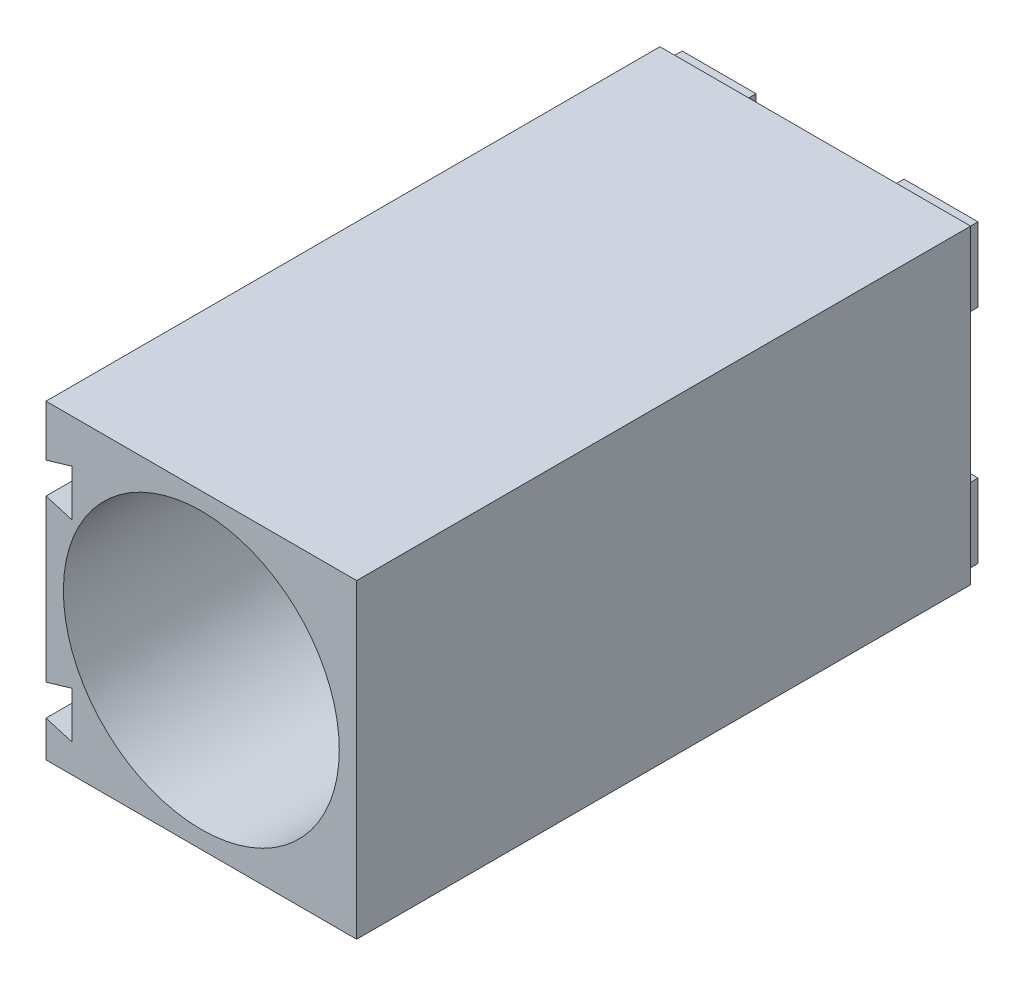
SolidWorks part; units mm, degrees
ref_plane "Front Plane" through (0, 0, 0) normal (0, 0, 1) x (1, 0, 0)
ref_plane "Top Plane" through (0, 0, 0) normal (0, 1, 0) x (1, 0, 0)
ref_plane "Right Plane" through (0, 0, 0) normal (1, 0, 0) x (0, 0, -1)
sketch "Croquis1" plane through (0, 0, 0) normal (0, 0, 1) x (1, 0, 0)
  line L0 (31.5, -10.5) -> (10.5, 10.5) construction
  line L1 (-10.5, 10.5) -> (31.5, 10.5)
  line L2 (-10.5, 10.5) -> (-10.5, -10.5)
  line L3 (-10.5, -10.5) -> (31.5, -10.5)
  line L4 (10.5, 10.5) -> (10.5, -10.5)
  line L5 (-10.5, 10.5) -> (10.5, -10.5) construction
  line L6 (-10.5, -10.5) -> (10.5, 10.5) construction
  line L7 (31.5, 10.5) -> (10.5, -10.5) construction
  line L8 (31.5, 10.5) -> (31.5, -10.5)
  circle A0 centre (0, 0) radius 9.325
  circle A1 centre (21, 0) radius 9.325
  point P0 (0, 0)
  point P12 (21, 0)
  dimension "D3" = 18.65
  dimension "D1" = 21
  dimension "D2" = 21
extrude "Saliente-Extruir1" add sketch "Croquis1" along normal mid plane 41.5 contours L4 L1 L2 L3 A0
sketch "Croquis2" plane through (0, 0, -20.75) normal (0, 0, -1) x (-1, 0, 0)
  line L0 (-10.5, 10.5) -> (-10.5, -10.5) construction
  line L1 (-10, 10) -> (-5, 10)
  line L2 (-10, 10) -> (-10, 5)
  line L3 (-10, 5) -> (-5, 5)
  line L4 (-5, 10) -> (-5, 5)
  line L5 (-10, 10) -> (-5, 5) construction
  line L6 (-10, 5) -> (-5, 10) construction
  line L7 (10.5, 10.5) -> (-10.5, 10.5) construction
  line L8 (0, 0) -> (10.5, 0) construction
  line L9 (10.5, 10.5) -> (10.5, -10.5) construction
  line L10 (0, 0) -> (0, 10.5) construction
  line L11 (10, 5) -> (5, 10) construction
  line L12 (10, 10) -> (5, 5) construction
  line L13 (5, 10) -> (5, 5)
  line L14 (10, 5) -> (5, 5)
  line L15 (10, 10) -> (10, 5)
  line L16 (10, 10) -> (5, 10)
  line L17 (10, -10) -> (5, -5) construction
  line L18 (10, -5) -> (5, -10) construction
  line L19 (10, -10) -> (5, -10)
  line L20 (10, -10) -> (10, -5)
  line L21 (10, -5) -> (5, -5)
  line L22 (5, -10) -> (5, -5)
  line L23 (-10, -5) -> (-5, -10) construction
  line L24 (-10, -10) -> (-5, -5) construction
  line L25 (-5, -10) -> (-5, -5)
  line L26 (-10, -5) -> (-5, -5)
  line L27 (-10, -10) -> (-10, -5)
  line L28 (-10, -10) -> (-5, -10)
  line L29 (-10.5, -10.5) -> (-10.5, 10.5) construction
  line L30 (-11, -10) -> (-16, -5) construction
  line L31 (-11, -5) -> (-16, -10) construction
  line L32 (-31, -5) -> (-26, -10) construction
  line L33 (-31, -10) -> (-26, -5) construction
  line L34 (-31, 10) -> (-26, 5) construction
  line L35 (-31, 5) -> (-26, 10) construction
  line L36 (-11, 5) -> (-16, 10) construction
  line L37 (-11, 10) -> (-16, 5) construction
  line L38 (-11, -10) -> (-16, -10)
  line L39 (-11, -10) -> (-11, -5)
  line L40 (-11, -5) -> (-16, -5)
  line L41 (-16, -10) -> (-16, -5)
  line L42 (-26, -10) -> (-26, -5)
  line L43 (-31, -5) -> (-26, -5)
  line L44 (-31, -10) -> (-31, -5)
  line L45 (-31, -10) -> (-26, -10)
  line L46 (-31, 10) -> (-26, 10)
  line L47 (-31, 10) -> (-31, 5)
  line L48 (-31, 5) -> (-26, 5)
  line L49 (-26, 10) -> (-26, 5)
  line L50 (-16, 10) -> (-16, 5)
  line L51 (-11, 5) -> (-16, 5)
  line L52 (-11, 10) -> (-11, 5)
  line L53 (-11, 10) -> (-16, 10)
  point P0 (-7.5, 7.5)
  point P19 (7.5, 7.5)
  point P24 (7.5, -7.5)
  point P29 (-7.5, -7.5)
  point P50 (-13.5, -7.5)
  point P51 (-28.5, -7.5)
  point P52 (-28.5, 7.5)
  point P53 (-13.5, 7.5)
  dimension "D1" = 5
  dimension "D2" = 5
  dimension "D3" = 0.5
  dimension "D4" = 0.5
extrude "Saliente-Extruir3" add sketch "Croquis2" along normal blind 1 contours L27 L26 L25 L28 | L3 L4 L1 L2 | L22 L21 L20 L19 | L14 L13 L16 L15
sketch "Croquis8" plane through (0, 0, 20.75) normal (0, 0, 1) x (1, 0, 0)
  line L0 (-10.5, -6) -> (-8.8, -5.5)
  line L1 (-10.5, 10.5) -> (-10.5, -10.5) construction
  line L2 (-8.8, -5.5) -> (-8.8, -8.5)
  line L3 (-8.8, -8.5) -> (-10.5, -8)
  line L4 (-10.5, -8) -> (-10.5, -6)
  line L6 (-10.5, -10.5) -> (10.5, -10.5) construction
  line L12 (-10.55, -5.9626) -> (-8.75, -5.4332)
  line L13 (-8.75, -5.4332) -> (-8.75, -8.5668)
  line L14 (-8.75, -8.5668) -> (-10.55, -8.0374)
  line L15 (-10.55, -8.0374) -> (-10.55, -5.9626)
  line L21 (-10.5, -0.5) -> (10.5, -0.5) construction
  line L22 (10.5, 10.5) -> (10.5, -10.5) construction
  line L23 (-10.55, 7.0374) -> (-10.55, 4.9626)
  line L24 (-8.75, 7.5668) -> (-10.55, 7.0374)
  line L25 (-8.75, 4.4332) -> (-8.75, 7.5668)
  line L26 (-10.55, 4.9626) -> (-8.75, 4.4332)
  line L27 (-10.5, 7) -> (-10.5, 5)
  line L28 (-8.8, 7.5) -> (-10.5, 7)
  line L29 (-8.8, 4.5) -> (-8.8, 7.5)
  line L30 (-10.5, 5) -> (-8.8, 4.5)
  point P4 (-8.8, -7)
  dimension "D1" = 1.7
  dimension "D2" = 0.5
  dimension "D3" = 3
  dimension "D4" = 3.5
  dimension "D6" = 6.5
  dimension "D5" = 0.05
extrude "Cortar-Extruir2" cut sketch "Croquis8" against normal blind 18 contours L25 L24 L23 L26 | L14 L15 L12 L13
sketch "Croquis9" plane through (0, 0, -20.75) normal (0, 0, -1) x (-1, 0, 0)
  line L0 (6, -10.5) -> (8, -10.5)
  line L1 (10.5, -10.5) -> (-10.5, -10.5) construction
  line L2 (8, -10.5) -> (8.5, -12.2)
  line L3 (8.5, -12.2) -> (5.5, -12.2)
  line L4 (5.5, -12.2) -> (6, -10.5)
  line L6 (10.5, 10.5) -> (10.5, -10.5) construction
  line L11 (0.5, 10.5) -> (0.5, -10.5) construction
  line L12 (10.5, 10.5) -> (-10.5, 10.5) construction
  line L13 (-4.5, -12.2) -> (-5, -10.5)
  line L14 (-7.5, -12.2) -> (-4.5, -12.2)
  line L15 (-7, -10.5) -> (-7.5, -12.2)
  line L16 (-5, -10.5) -> (-7, -10.5)
  point P4 (7, -12.2)
  dimension "D1" = 0.5
  dimension "D2" = 1.7
  dimension "D3" = 3
  dimension "D4" = 3.5
  dimension "D5" = 6.5
extrude "Saliente-Extruir7" add sketch "Croquis9" against normal blind 8
equation "\"D2@Croquis1\"=\"D1@Croquis1\""
